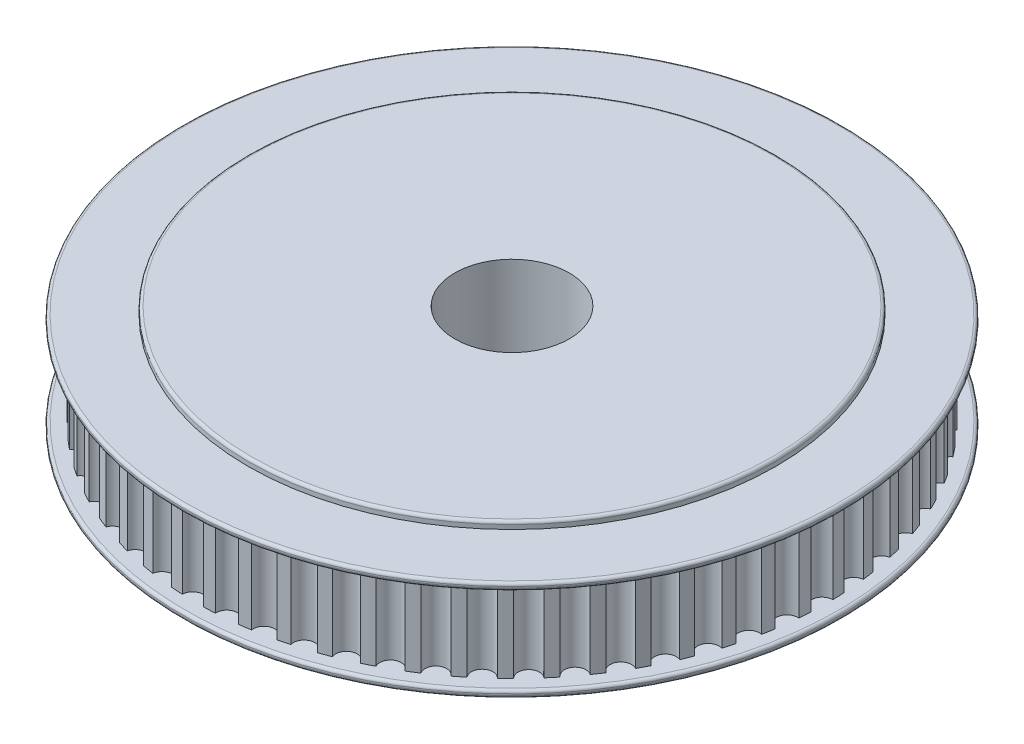
SolidWorks part; units mm, degrees
ref_plane "Front Plane" through (0, 0, 0) normal (0, 0, 1) x (1, 0, 0)
ref_plane "Top Plane" through (0, 0, 0) normal (0, 1, 0) x (1, 0, 0)
ref_plane "Right Plane" through (0, 0, 0) normal (1, 0, 0) x (0, 0, -1)
sketch "Sketch1" plane through (0, 0, 0) normal (0, 1, 0) x (1, 0, 0)
  circle A0 centre (0, 0) radius 22
  dimension "D1" = 44
extrude "Boss-Extrude1" add sketch "Sketch1" along normal blind 6
sketch "Sketch2" plane through (0, 6, 0) normal (0, 1, 0) x (1, 0, 0)
  circle A0 centre (-4.2593, 21.5838) radius 0.75
  circle A1 centre (0, 0) radius 22 construction
  circle A2 centre (-1.9798, 21.9107) radius 0.75
  circle A3 centre (0.3213, 21.9977) radius 0.75
  circle A4 centre (2.6189, 21.8436) radius 0.75
  circle A5 centre (4.8878, 21.4502) radius 0.75
  circle A6 centre (7.1032, 20.8217) radius 0.75
  circle A7 centre (9.2408, 19.9652) radius 0.75
  circle A8 centre (11.2771, 18.8899) radius 0.75
  circle A9 centre (13.1898, 17.6076) radius 0.75
  circle A10 centre (14.9581, 16.1325) radius 0.75
  circle A11 centre (16.5624, 14.4805) radius 0.75
  circle A12 centre (17.9853, 12.67) radius 0.75
  circle A13 centre (19.2112, 10.7206) radius 0.75
  circle A14 centre (20.2265, 8.6537) radius 0.75
  circle A15 centre (21.0203, 6.4921) radius 0.75
  circle A16 centre (21.5838, 4.2593) radius 0.75
  circle A17 centre (21.9107, 1.9798) radius 0.75
  circle A18 centre (21.9977, -0.3213) radius 0.75
  circle A19 centre (21.8436, -2.6189) radius 0.75
  circle A20 centre (21.4502, -4.8878) radius 0.75
  circle A21 centre (20.8217, -7.1032) radius 0.75
  circle A22 centre (19.9652, -9.2408) radius 0.75
  circle A23 centre (18.8899, -11.2771) radius 0.75
  circle A24 centre (17.6076, -13.1898) radius 0.75
  circle A25 centre (16.1325, -14.9581) radius 0.75
  circle A26 centre (14.4805, -16.5624) radius 0.75
  circle A27 centre (12.67, -17.9853) radius 0.75
  circle A28 centre (10.7206, -19.2112) radius 0.75
  circle A29 centre (8.6537, -20.2265) radius 0.75
  circle A30 centre (6.4921, -21.0203) radius 0.75
  circle A31 centre (4.2593, -21.5838) radius 0.75
  circle A32 centre (1.9798, -21.9107) radius 0.75
  circle A33 centre (-0.3213, -21.9977) radius 0.75
  circle A34 centre (-2.6189, -21.8436) radius 0.75
  circle A35 centre (-4.8878, -21.4502) radius 0.75
  circle A36 centre (-7.1032, -20.8217) radius 0.75
  circle A37 centre (-9.2408, -19.9652) radius 0.75
  circle A38 centre (-11.2771, -18.8899) radius 0.75
  circle A39 centre (-13.1898, -17.6076) radius 0.75
  circle A40 centre (-14.9581, -16.1325) radius 0.75
  circle A41 centre (-16.5624, -14.4805) radius 0.75
  circle A42 centre (-17.9853, -12.67) radius 0.75
  circle A43 centre (-19.2112, -10.7206) radius 0.75
  circle A44 centre (-20.2265, -8.6537) radius 0.75
  circle A45 centre (-21.0203, -6.4921) radius 0.75
  circle A46 centre (-21.5838, -4.2593) radius 0.75
  circle A47 centre (-21.9107, -1.9798) radius 0.75
  circle A48 centre (-21.9977, 0.3213) radius 0.75
  circle A49 centre (-21.8436, 2.6189) radius 0.75
  circle A50 centre (-21.4502, 4.8878) radius 0.75
  circle A51 centre (-20.8217, 7.1032) radius 0.75
  circle A52 centre (-19.9652, 9.2408) radius 0.75
  circle A53 centre (-18.8899, 11.2771) radius 0.75
  circle A54 centre (-17.6076, 13.1898) radius 0.75
  circle A55 centre (-16.1325, 14.9581) radius 0.75
  circle A56 centre (-14.4805, 16.5624) radius 0.75
  circle A57 centre (-12.67, 17.9853) radius 0.75
  circle A58 centre (-10.7206, 19.2112) radius 0.75
  circle A59 centre (-8.6537, 20.2265) radius 0.75
  circle A60 centre (-6.4921, 21.0203) radius 0.75
  dimension "D1" = 1.5
  dimension "D2" = 60
extrude "Cut-Extrude1" cut sketch "Sketch2" against normal blind 6
sketch "Sketch3" plane through (0, 6, 0) normal (0, 1, 0) x (1, 0, 0)
  circle A0 centre (0, 0) radius 23.0324
extrude "Boss-Extrude2" add sketch "Sketch3" along normal blind 0.5
sketch "Sketch4" plane through (0, 6.5, 0) normal (0, 1, 0) x (1, 0, 0)
  circle A0 centre (0, 0) radius 18.4378
extrude "Boss-Extrude3" add sketch "Sketch4" along normal blind 0.5
sketch "Sketch5" plane through (0, 0, 0) normal (0, -1, 0) x (1, 0, 0)
  circle A0 centre (0, 0) radius 23.0324
extrude "Boss-Extrude4" add sketch "Sketch5" along normal blind 0.5
sketch "Sketch6" plane through (0, -0.5, 0) normal (0, -1, 0) x (1, 0, 0)
  circle A0 centre (0, 0) radius 12.5
  dimension "D1" = 25
extrude "Boss-Extrude5" add sketch "Sketch6" along normal blind 6
fillet "Fillet2" radius 0.2 6 edges at (0, -6.5, -12.5) (0, -0.5, -23.0324) (0, 0, -23.0324) (0, 6, 23.0324) (0, 6.5, 23.0324) (0, 7, 18.4378)
sketch "Sketch7" plane through (0, 7, 0) normal (0, 1, 0) x (1, 0, 0)
  circle A0 centre (0, 0) radius 4
  dimension "D1" = 8
extrude "Cut-Extrude2" cut sketch "Sketch7" against normal through all
